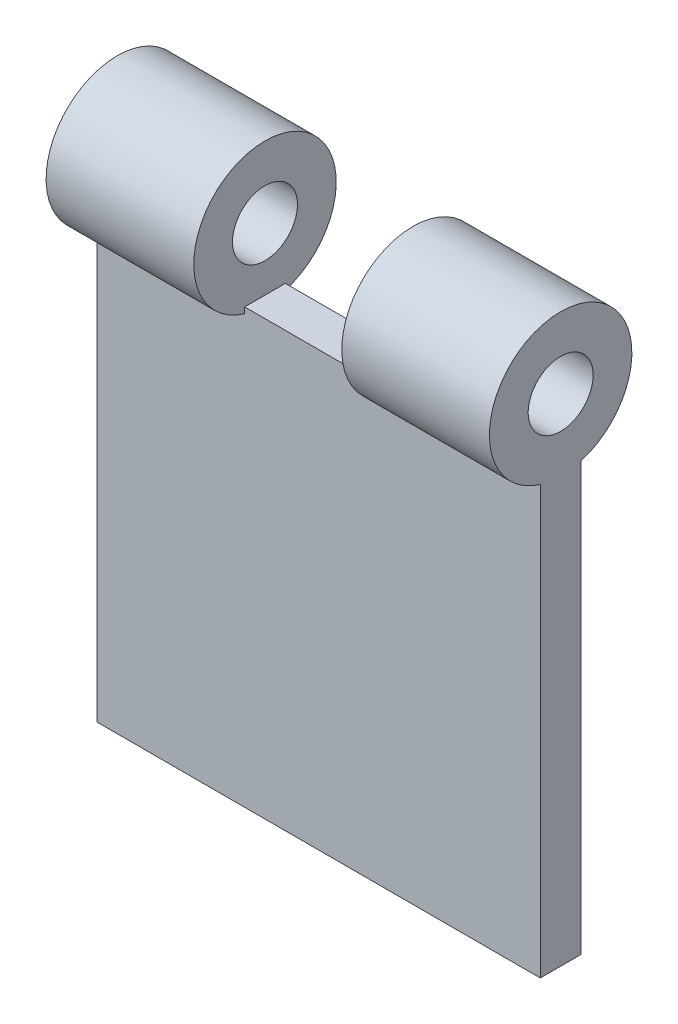
SolidWorks part; units mm, degrees
ref_plane "Front Plane" through (0, 0, 0) normal (0, 0, 1) x (1, 0, 0)
ref_plane "Top Plane" through (0, 0, 0) normal (0, 1, 0) x (1, 0, 0)
ref_plane "Right Plane" through (0, 0, 0) normal (1, 0, 0) x (0, 0, -1)
sketch "Sketch1" plane through (0, 0, 0) normal (0, 0, 1) x (1, 0, 0)
  line L1 (-24.278, 7.5938) -> (0.614, 7.5938)
  line L2 (-24.278, 7.5938) -> (-24.278, -0.2802)
  line L3 (-24.278, -0.2802) -> (0.614, -0.2802)
  line L4 (0.614, 7.5938) -> (0.614, -0.2802)
  dimension "D1" = 24.892
  dimension "D2" = 7.874
extrude "Boss-Extrude1" add sketch "Sketch1" along normal blind 2.286 contours L1 L4 L3 L2
sketch "Sketch2" plane through (0.614, 0, 0) normal (1, 0, 0) x (0, 0, -1)
  line L0 (-1.143, 7.5938) -> (-1.143, 11.0938) construction
  line L1 (-2.286, 7.5938) -> (0, 7.5938) construction
  circle A0 centre (-1.143, 11.0938) radius 4
  dimension "D1" = 8
  dimension "D2" = 3.5
extrude "Boss-Extrude2" add sketch "Sketch2" against normal blind 8.29 separate body contours A0
sketch "Sketch3" plane through (0.614, 0, 0) normal (1, 0, 0) x (0, 0, -1)
  circle A0 centre (-1.143, 11.0938) radius 1.825
  dimension "D1" = 3.65
extrude "Cut-Extrude1" cut sketch "Sketch3" against normal blind 8.29
sketch "Sketch4" plane through (-24.278, 0, 0) normal (-1, 0, 0) x (0, 0, 1)
  line L0 (1.143, 7.5938) -> (1.143, 11.0938) construction
  line L1 (2.286, 7.5938) -> (0, 7.5938) construction
  circle A0 centre (1.143, 11.0938) radius 4
  dimension "D1" = 8
  dimension "D2" = 3.5
extrude "Boss-Extrude3" add sketch "Sketch4" against normal blind 8.29
sketch "Sketch5" plane through (-24.278, 0, 0) normal (-1, 0, 0) x (0, 0, 1)
  circle A0 centre (1.143, 11.0938) radius 1.825
  dimension "D1" = 3.65
extrude "Cut-Extrude2" cut sketch "Sketch5" against normal blind 8.29
sketch "Sketch7" plane through (-24.278, 0, 0) normal (-1, 0, 0) x (0, 0, 1)
  line L0 (2.286, 7.2606) -> (2.286, -0.2802) construction
  line L1 (0, 7.2606) -> (2.286, 7.2606)
  line L2 (0, 7.2606) -> (0, -16.7394)
  line L3 (0, -16.7394) -> (2.286, -16.7394)
  line L4 (2.286, 7.2606) -> (2.286, -16.7394)
  dimension "D1" = 24
extrude "Boss-Extrude4" add sketch "Sketch7" against normal up to surface (24.892 mm away) up to face at (0.614, 3.6568, 1.143)
